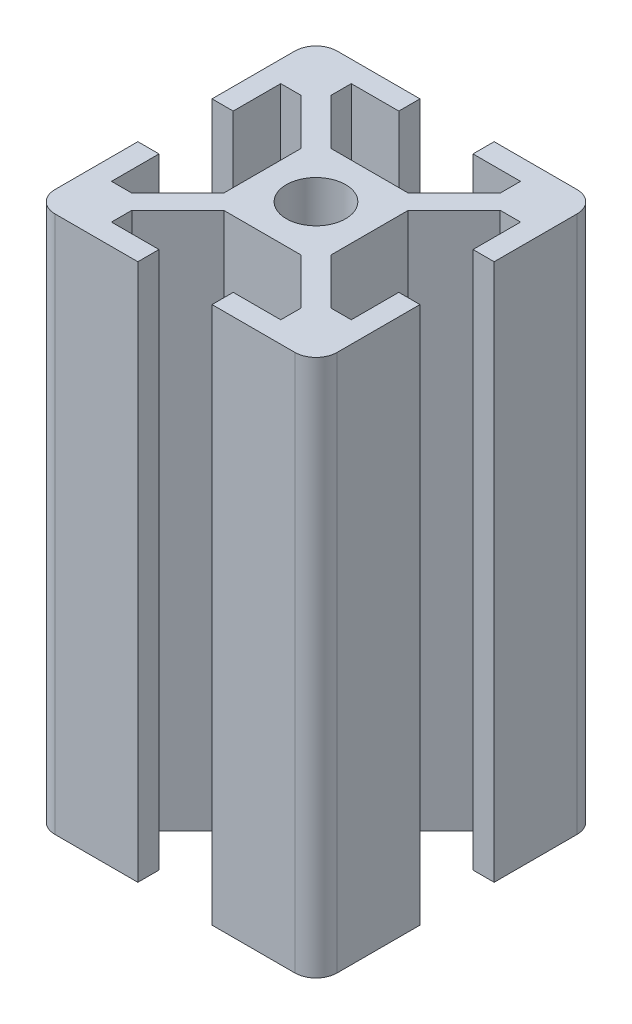
SolidWorks part; units mm, degrees
material "6063-T5"
ref_plane "Front Plane" through (0, 0, 0) normal (0, 0, 1) x (1, 0, 0)
ref_plane "Top Plane" through (0, 0, 0) normal (0, 1, 0) x (1, 0, 0)
ref_plane "Right Plane" through (0, 0, 0) normal (1, 0, 0) x (0, 0, -1)
sketch "Sketch1" plane through (0, 0, 0) normal (0, 1, 0) x (1, 0, 0)
  line L1 (-8.5, -10) -> (8.5, -10)
  line L2 (-10, -8.5) -> (-10, 8.5)
  line L3 (-8.5, 10) -> (8.5, 10)
  line L4 (10, -8.5) -> (10, 8.5)
  line L5 (-10, -10) -> (10, 10) construction
  line L6 (-10, 10) -> (10, -10) construction
  arc A0 (-8.5, -10) -> (-10, -8.5) centre (-8.5, -8.5) cw
  arc A1 (8.5, -10) -> (10, -8.5) centre (8.5, -8.5) ccw
  arc A2 (8.5, 10) -> (10, 8.5) centre (8.5, 8.5) cw
  arc A3 (-10, 8.5) -> (-8.5, 10) centre (-8.5, 8.5) cw
  point P0 (0, 0)
  dimension "D3" = 1.5
  dimension "D1" = 20
  dimension "D2" = 20
extrude "Boss-Extrude1" add sketch "Sketch1" along normal mid plane 38.1
sketch "Sketch3" plane through (0, 0, 0) normal (0, 1, 0) x (1, 0, 0)
  line L0 (-23.0759, 0) -> (23.0759, 0) construction
  line L1 (0, -18.6473) -> (0, 18.6473) construction
  line L2 (-2.63, 10) -> (2.63, 10)
  line L3 (8.5, 10) -> (-8.5, 10) construction
  line L4 (-6, 8.5) -> (-2.63, 8.5)
  line L5 (2.63, 8.5) -> (6, 8.5)
  line L6 (10, 2.63) -> (10, -2.63)
  line L7 (-3.8, 3.8) -> (2.7393, 3.8)
  line L8 (6, 8.5) -> (6, 7.0607)
  line L9 (2.63, 10) -> (2.63, 8.5)
  line L10 (-2.63, 10) -> (-2.63, 8.5)
  line L11 (10, 2.63) -> (8.5, 2.63)
  line L12 (10, -2.63) -> (8.5, -2.63)
  line L13 (-6, 8.5) -> (-6, 7.0607)
  line L14 (2.7393, 3.8) -> (6, 7.0607)
  line L15 (8.5, -2.63) -> (8.5, -6)
  line L16 (8.5, -6) -> (7.0607, -6)
  line L17 (3.8, -2.7393) -> (7.0607, -6)
  line L18 (3.8, 3.8) -> (3.8, -2.7393)
  line L19 (-2.7393, 3.8) -> (-6, 7.0607)
  line L20 (3.8, 2.7393) -> (7.0607, 6)
  line L21 (8.5, 6) -> (7.0607, 6)
  line L22 (8.5, 6) -> (8.5, 2.63)
  line L23 (2.63, -10) -> (-2.63, -10)
  line L24 (2.63, -10) -> (2.63, -8.5)
  line L25 (-2.63, -10) -> (-2.63, -8.5)
  line L26 (-2.63, -8.5) -> (-6, -8.5)
  line L27 (-6, -8.5) -> (-6, -7.0607)
  line L28 (-2.7393, -3.8) -> (-6, -7.0607)
  line L29 (3.8, -3.8) -> (-2.7393, -3.8)
  line L30 (2.7393, -3.8) -> (6, -7.0607)
  line L31 (6, -8.5) -> (6, -7.0607)
  line L32 (6, -8.5) -> (2.63, -8.5)
  line L33 (-10, -2.63) -> (-10, 2.63)
  line L34 (-10, -2.63) -> (-8.5, -2.63)
  line L35 (-10, 2.63) -> (-8.5, 2.63)
  line L36 (-8.5, 2.63) -> (-8.5, 6)
  line L37 (-8.5, 6) -> (-7.0607, 6)
  line L38 (-3.8, 2.7393) -> (-7.0607, 6)
  line L39 (-3.8, -3.8) -> (-3.8, 2.7393)
  line L40 (-3.8, -2.7393) -> (-7.0607, -6)
  line L41 (-8.5, -6) -> (-7.0607, -6)
  line L42 (-8.5, -6) -> (-8.5, -2.63)
  circle A0 centre (0, 0) radius 2.5 construction
  point P4 (0, 0)
  point P8 (0, 0)
  point P12 (0, 10)
  point P15 (0, 8.5)
  point P17 (-10.091, -9.0303)
  point P18 (9.5607, 9.5607)
  point P19 (-9.5607, -9.5607)
  point P23 (0, 0)
  point P24 (9.0303, 10.091)
  point P25 (10.091, -9.0303)
  point P28 (0, 3.8)
  point P32 (-9.5607, 9.5607)
  point P33 (9.5607, -9.5607)
  point P37 (0, 0)
  point P38 (-9.0303, 10.091)
  point P71 (0, 0)
  dimension "D3" = 5
  dimension "D1" = 1.5
  dimension "D2" = 12
  dimension "D5" = 4.7
  dimension "D4" = 4
extrude "Cut-Extrude5" cut sketch "Sketch3" against normal through all and the other way through all contours L19 L7 L14 L8 L5 L9 L2 L10 L4 L13 | L22 L21 L20 L18 L17 L16 L15 L12 L6 L11 | L32 L31 L30 L29 L28 L27 L26 L25 L23 L24 | L42 L41 L40 L39 L38 L37 L36 L35 L33 L34 | A0
sketch "Sketch4" plane through (0, 19.05, 0) normal (0, 1, 0) x (1, 0, 0)
  circle A0 centre (0, 0) radius 2.1
  dimension "D1" = 4.2
sketch "Sketch5" plane through (0, -19.05, 0) normal (0, -1, 0) x (1, 0, 0)
  circle A0 centre (0, 0) radius 2.1
  dimension "D1" = 4.2
extrude "Cut-Extrude6" cut sketch "Sketch5" against normal blind 13
extrude "Cut-Extrude7" cut sketch "Sketch4" against normal blind 13
